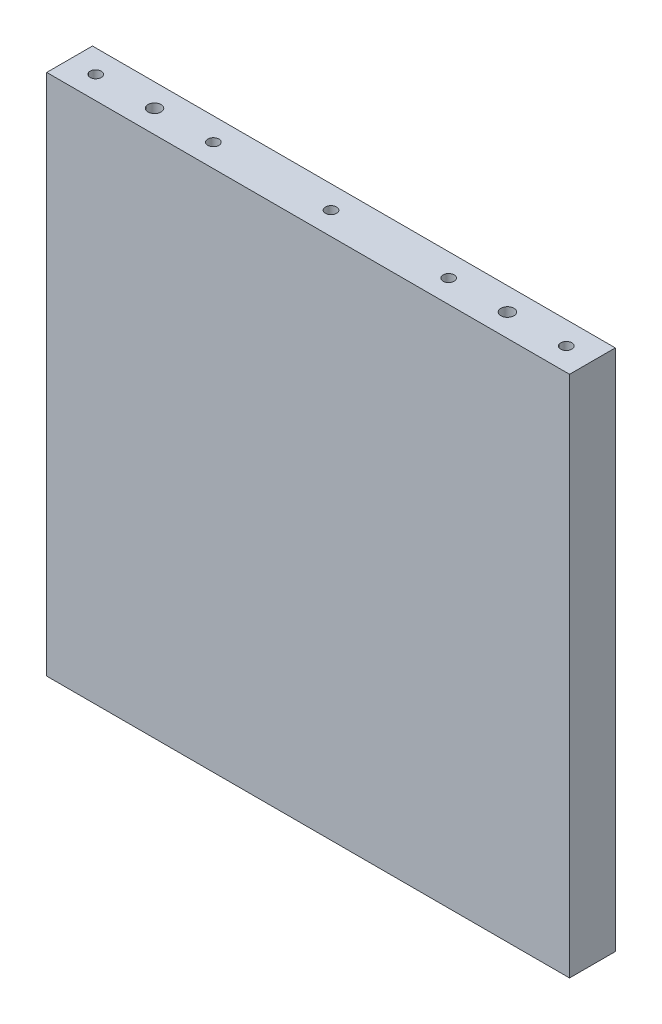
SolidWorks part; units mm, degrees
ref_plane "Plano frontal" through (0, 0, 0) normal (0, 0, 1) x (1, 0, 0)
ref_plane "Plano superior" through (0, 0, 0) normal (0, 1, 0) x (1, 0, 0)
ref_plane "Plano direito" through (0, 0, 0) normal (1, 0, 0) x (0, 0, -1)
sketch "Esboço1" plane through (0, 0, 0) normal (0, 0, 1) x (1, 0, 0)
  line L1 (-200, 200) -> (200, 200)
  line L2 (-200, 200) -> (-200, -200)
  line L3 (-200, -200) -> (200, -200)
  line L4 (200, 200) -> (200, -200)
  dimension "D1" = 400
  dimension "D2" = 200
  dimension "D3" = 400
  dimension "D4" = 200
extrude "Ressalto-extrusão1" add sketch "Esboço1" along normal blind 35
hole_wizard "Furo roscado de M103" positions "Esboço10" profile "Esboço11" tap size "M10" standard "DIN"
sketch "Esboço10" plane through (0, 200, 0) normal (0, 1, 0) x (1, 0, 0)
  line L0 (200, -35) -> (-200, -35) construction
  line L1 (-200, -35) -> (-200, 0) construction
  line L2 (200, -35) -> (200, 0) construction
  point P0 (-180, -17.5)
  point P2 (-90, -17.5)
  point P4 (0, -17.5)
  point P6 (90, -17.5)
  point P8 (180, -17.5)
  dimension "D1" = 17.5
  dimension "D2" = 20
  dimension "D3" = 90
  dimension "D4" = 90
  dimension "D5" = 20
  dimension "D6" = 90
sketch "Esboço11" plane through (-180, 200, 17.5) normal (1, 0, 0) x (0, 0, 1)
  line L0 (0, 0) -> (0, 30.0537)
  line L1 (0, 30.0537) -> (4.25, 27.5)
  line L2 (4.25, 27.5) -> (4.25, 0)
  line L5 (4.25, 0) -> (0, 0)
  line L10 (0, 30.0537) -> (-4.25, 27.5) construction
  line L11 (0, -6.35) -> (0, 107.95) construction
  dimension "Tap Drill Dia." = 8.5
  dimension "Tap Drill Depth" = 27.5
  dimension "Drill Angle" = 118
cosmetic thread "Rosca de furo11"
cosmetic thread "Rosca de furo12"
cosmetic thread "Rosca de furo13"
cosmetic thread "Rosca de furo14"
cosmetic thread "Rosca de furo15"
hole_wizard "Furo roscado de M104" positions "Esboço12" profile "Esboço13" tap size "M10" standard "DIN"
sketch "Esboço12" plane through (0, -200, 0) normal (0, -1, 0) x (-1, 0, 0)
  line L0 (200, 0) -> (-200, 0) construction
  line L1 (-200, -35) -> (-200, 0) construction
  line L3 (200, -35) -> (200, 0) construction
  point P0 (180, -17.5)
  point P2 (90, -17.5)
  point P4 (0, -17.5)
  point P6 (-90, -17.5)
  point P8 (-180, -17.5)
  point P17 (0, 0)
  dimension "D1" = 17.5
  dimension "D2" = 20
  dimension "D3" = 90
  dimension "D4" = 90
  dimension "D5" = 20
  dimension "D6" = 90
sketch "Esboço13" plane through (-180, -200, 17.5) normal (1, 0, 0) x (0, 0, -1)
  line L0 (0, 0) -> (0, 30.0537)
  line L1 (0, 30.0537) -> (4.25, 27.5)
  line L2 (4.25, 27.5) -> (4.25, 0)
  line L5 (4.25, 0) -> (0, 0)
  line L10 (0, 30.0537) -> (-4.25, 27.5) construction
  line L11 (0, -6.35) -> (0, 107.95) construction
  dimension "Tap Drill Dia." = 8.5
  dimension "Tap Drill Depth" = 27.5
  dimension "Drill Angle" = 118
cosmetic thread "Rosca de furo16"
cosmetic thread "Rosca de furo17"
cosmetic thread "Rosca de furo18"
cosmetic thread "Rosca de furo19"
cosmetic thread "Rosca de furo20"
hole_wizard "Furos-guia com Ø10.0mm3" positions "Esboço14" profile "Esboço15" hole size "Ø10.0" standard "DIN"
sketch "Esboço14" plane through (0, -200, 0) normal (0, -1, 0) x (-1, 0, 0)
  line L0 (200, -35) -> (200, 0) construction
  line L1 (-200, -35) -> (-200, 0) construction
  line L2 (200, 0) -> (-200, 0) construction
  point P0 (135, -17.5)
  point P2 (-135, -17.5)
  dimension "D1" = 65
  dimension "D2" = 65
  dimension "D3" = 17.5
sketch "Esboço15" plane through (-135, -200, 17.5) normal (1, 0, 0) x (0, 0, -1)
  line L0 (0, 0) -> (0, 30.5043)
  line L1 (0, 30.5043) -> (5, 27.5)
  line L2 (5, 27.5) -> (5, 0)
  line L5 (5, 0) -> (0, 0)
  line L10 (0, 30.5043) -> (-5, 27.5) construction
  line L11 (0, -6.35) -> (0, 107.95) construction
  dimension "Hole Dia." = 10
  dimension "Hole Depth" = 27.5
  dimension "Drill Angle" = 118
hole_wizard "Furos-guia com Ø10.0mm4" positions "Esboço16" profile "Esboço17" hole size "Ø10.0" standard "DIN"
sketch "Esboço16" plane through (0, 200, 0) normal (0, 1, 0) x (1, 0, 0)
  line L0 (-200, -35) -> (-200, 0) construction
  line L1 (200, -35) -> (200, 0) construction
  line L2 (200, -35) -> (-200, -35) construction
  point P0 (-135, -17.5)
  point P2 (135, -17.5)
  dimension "D1" = 65
  dimension "D2" = 65
  dimension "D3" = 17.5
sketch "Esboço17" plane through (-135, 200, 17.5) normal (1, 0, 0) x (0, 0, 1)
  line L0 (0, 0) -> (0, 30.5043)
  line L1 (0, 30.5043) -> (5, 27.5)
  line L2 (5, 27.5) -> (5, 0)
  line L5 (5, 0) -> (0, 0)
  line L10 (0, 30.5043) -> (-5, 27.5) construction
  line L11 (0, -6.35) -> (0, 107.95) construction
  dimension "Hole Dia." = 10
  dimension "Hole Depth" = 27.5
  dimension "Drill Angle" = 118
